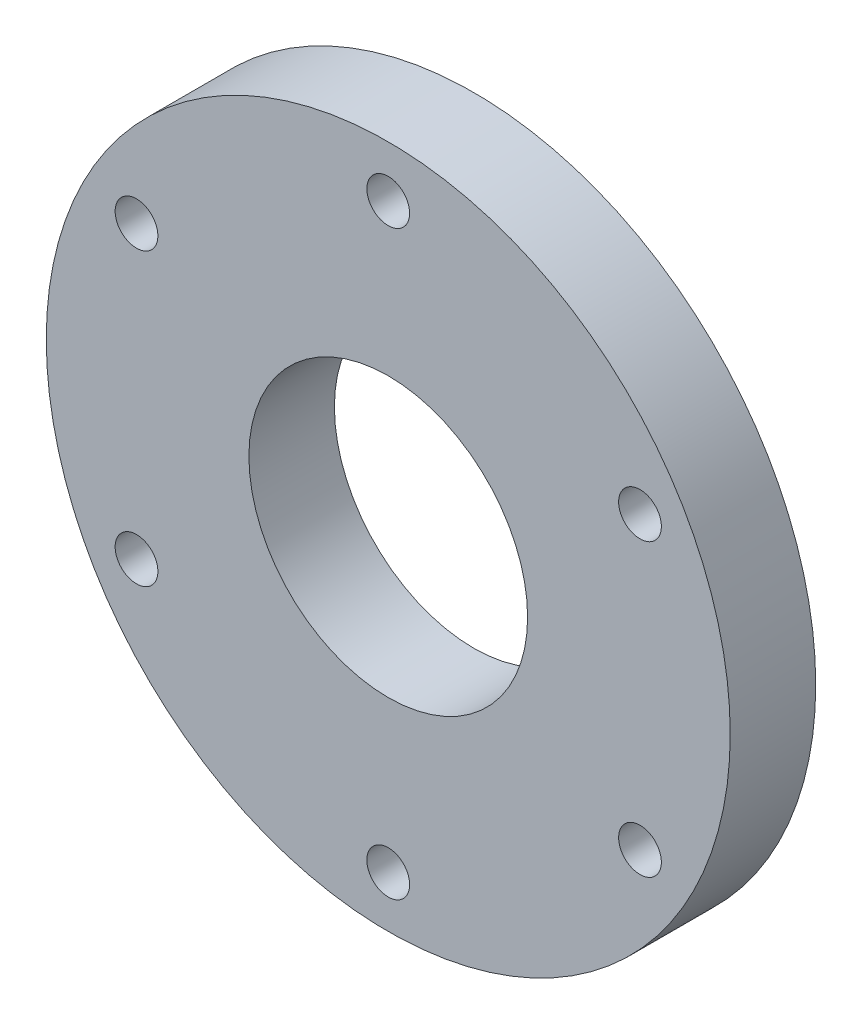
SolidWorks part; units mm, degrees
ref_plane "Front Plane" through (0, 0, 0) normal (0, 0, 1) x (1, 0, 0)
ref_plane "Top Plane" through (0, 0, 0) normal (0, 1, 0) x (1, 0, 0)
ref_plane "Right Plane" through (0, 0, 0) normal (1, 0, 0) x (0, 0, -1)
sketch "Sketch1" plane through (0, 0, 0) normal (0, 0, 1) x (1, 0, 0)
  line L0 (0, 0) -> (0, 17) construction
  circle A0 centre (0, 0) radius 20
  circle A1 centre (0, 0) radius 17 construction
  circle A2 centre (0, 17) radius 1.25
  circle A3 centre (14.7224, 8.5) radius 1.25
  circle A4 centre (14.7224, -8.5) radius 1.25
  circle A5 centre (0, -17) radius 1.25
  circle A6 centre (-14.7224, -8.5) radius 1.25
  circle A7 centre (-14.7224, 8.5) radius 1.25
  circle A8 centre (0, 0) radius 8.15
  point P19 (0, 0)
  dimension "D1" = 34
  dimension "D2" = 40
  dimension "D3" = 2.5
  dimension "D5" = 16.3
  dimension "D4" = 6
extrude "Boss-Extrude1" add sketch "Sketch1" along normal blind 5
